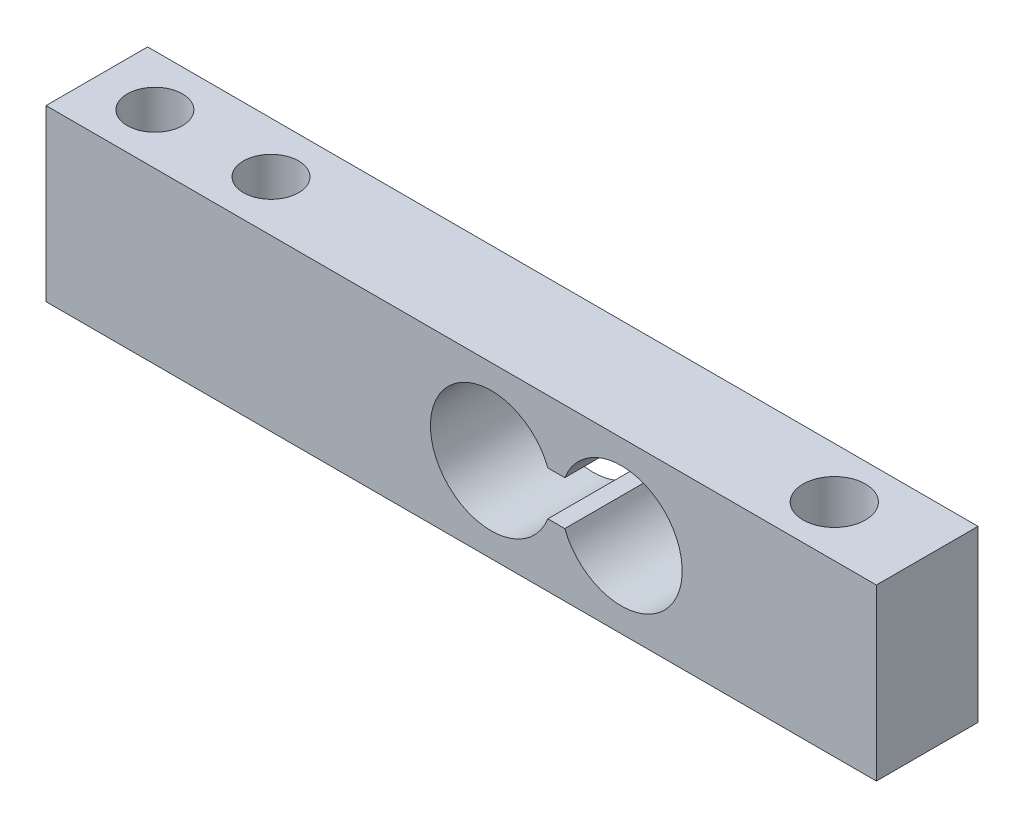
SolidWorks part; units mm, degrees
ref_plane "Front Plane" through (0, 0, 0) normal (0, 0, 1) x (1, 0, 0)
ref_plane "Top Plane" through (0, 0, 0) normal (0, 1, 0) x (1, 0, 0)
ref_plane "Right Plane" through (0, 0, 0) normal (1, 0, 0) x (0, 0, -1)
sketch "Sketch1" plane through (0, 0, 0) normal (0, 0, 1) x (1, 0, 0)
  line L1 (0, 0) -> (57.2, 0)
  line L2 (0, 0) -> (0, 11.7)
  line L3 (0, 11.7) -> (57.2, 11.7)
  line L4 (57.2, 0) -> (57.2, 11.7)
  dimension "D1" = 11.7
  dimension "D2" = 57.2
extrude "Boss-Extrude1" add sketch "Sketch1" along normal blind 7
sketch "Sketch2" plane through (0, 11.7, 0) normal (0, 1, 0) x (1, 0, 0)
  line L0 (0, -3.5) -> (57.2, -3.5) construction
  line L1 (0, -7) -> (0, 0) construction
  line L2 (57.2, -7) -> (57.2, 0) construction
  circle A0 centre (50.8, -3.5) radius 2.15
  circle A1 centre (4, -3.5) radius 1.9
  circle A2 centre (12, -3.5) radius 1.9
  dimension "D1" = 3.8
  dimension "D2" = 4.3
  dimension "D3" = 8
  dimension "D4" = 4
  dimension "D5" = 50.8
extrude "Cut-Extrude1" cut sketch "Sketch2" against normal through all both and the other way through all
sketch "Sketch3" plane through (0, 0, 7) normal (0, 0, 1) x (1, 0, 0)
  line L0 (0, 5.85) -> (57.2, 5.85) construction
  line L1 (0, 11.7) -> (0, 0) construction
  line L2 (57.2, 0) -> (57.2, 11.7) construction
  line L3 (34.5707, 7.3674) -> (35.7342, 7.3674)
  line L4 (35.7342, 4.3326) -> (34.5707, 4.3326)
  arc A0 (34.5707, 7.3674) -> (34.5707, 4.3326) centre (30.6684, 5.85) ccw
  arc A1 (35.7342, 4.3326) -> (35.7342, 7.3674) centre (39.6365, 5.85) ccw
extrude "Cut-Extrude2" cut sketch "Sketch3" against normal through all
